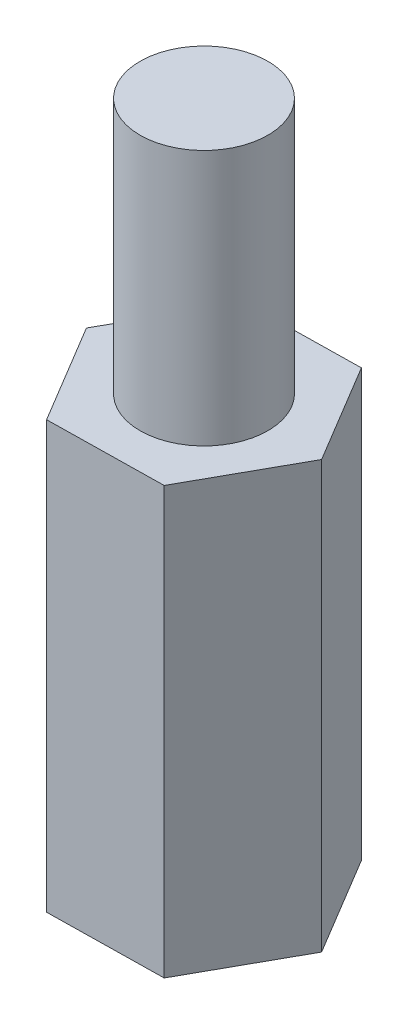
SolidWorks part; units mm, degrees
material "黄铜"
ref_plane "前视基准面" through (0, 0, 0) normal (0, 0, 1) x (1, 0, 0)
ref_plane "上视基准面" through (0, 0, 0) normal (0, 1, 0) x (1, 0, 0)
ref_plane "右视基准面" through (0, 0, 0) normal (1, 0, 0) x (0, 0, -1)
sketch "草图1" plane through (0, 0, 0) normal (0, 1, 0) x (1, 0, 0)
  line L0 (-5.8996, -0.071) -> (5.5773, 0.1142) construction
  line L1 (1.3945, -2.3278) -> (2.7132, 0.0438)
  line L2 (2.7132, 0.0438) -> (1.3187, 2.3716)
  line L3 (1.3187, 2.3716) -> (-1.3945, 2.3278)
  line L4 (-1.3945, 2.3278) -> (-2.7132, -0.0438)
  line L5 (-2.7132, -0.0438) -> (-1.3187, -2.3716)
  line L6 (-1.3187, -2.3716) -> (1.3945, -2.3278)
  circle A0 centre (0, 0) radius 2.35 construction
  circle A1 centre (0, 0) radius 1.5
  dimension "D3" = 3
  dimension "D1" = 4.7
  dimension "D2" = 60
extrude "凸台-拉伸1" add sketch "草图1" along normal blind 10
sketch "草图2" plane through (0, 10, 0) normal (0, 1, 0) x (1, 0, 0)
  circle A0 centre (0, 0) radius 1.5
  dimension "D1" = 3
extrude "凸台-拉伸2" add sketch "草图2" along normal blind 6 separate body
